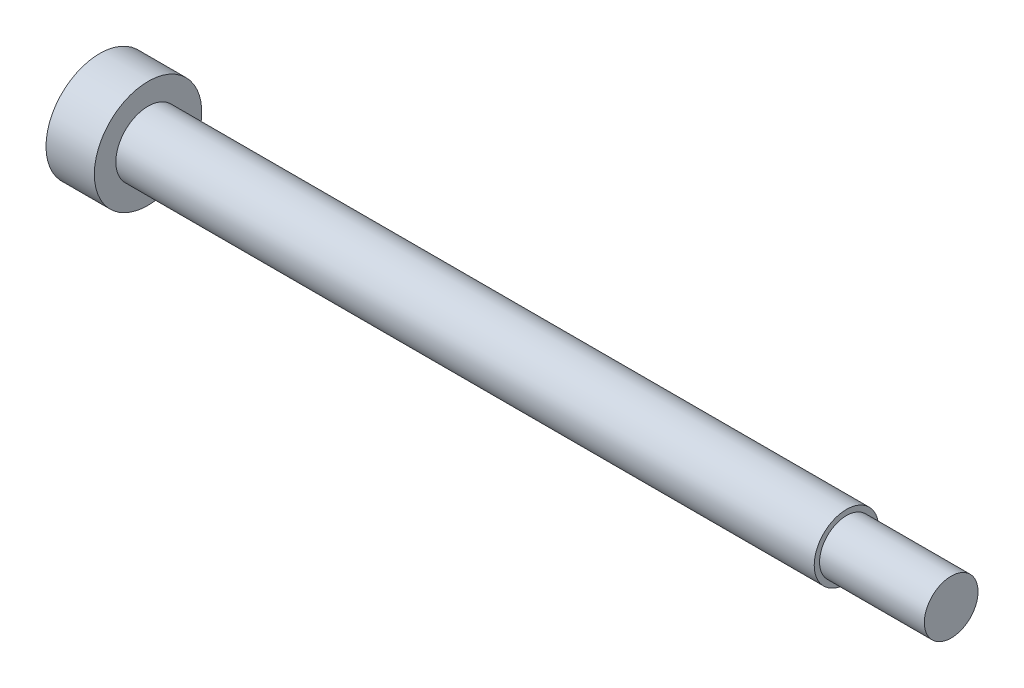
SolidWorks part; units mm, degrees
material "1060 合金"
ref_plane "前视基准面" through (0, 0, 0) normal (0, 0, 1) x (1, 0, 0)
ref_plane "上视基准面" through (0, 0, 0) normal (0, 1, 0) x (1, 0, 0)
ref_plane "右视基准面" through (0, 0, 0) normal (1, 0, 0) x (0, 0, -1)
other "Configuration Table"
sketch "草图1" plane through (0, 0, 0) normal (0, 0, 1) x (1, 0, 0)
  line L0 (0, 0) -> (10456.4321, 0) construction
  line L1 (0, 0) -> (0, 5)
  line L2 (0, 5) -> (4.5, 5)
  line L3 (4.5, 5) -> (4.5, 3)
  line L4 (4.5, 3) -> (69.5, 3)
  line L5 (69.5, 3) -> (69.5, 2.5)
  line L6 (69.5, 2.5) -> (79.25, 2.5)
  line L7 (79.25, 2.5) -> (79.25, 0)
  line L8 (79.25, 0) -> (0, 0)
  point P10 (76.1757, 1.3331)
  dimension "D1" = 5
  dimension "D2" = 3
  dimension "D3" = 4.5
  dimension "D4" = 65
  dimension "D5" = 2.5
  dimension "D6" = 9.75
revolve "旋转1" add sketch "草图1" angle 360 about L0
cosmetic thread "装饰螺纹线1" parameters "D2"=4
sketch "草图2" plane through (0, 0, 0) normal (-1, 0, 0) x (0, 0, 1)
  line L0 (0, 2.8868) -> (0, 0) construction
  line L1 (0, 2.8868) -> (-2.5, 1.4434)
  line L2 (-2.5, 1.4434) -> (-2.5, -1.4434)
  line L3 (-2.5, -1.4434) -> (0, -2.8868)
  line L4 (0, -2.8868) -> (2.5, -1.4434)
  line L5 (2.5, -1.4434) -> (2.5, 1.4434)
  line L6 (2.5, 1.4434) -> (0, 2.8868)
  circle A0 centre (0, 0) radius 2.5 construction
  dimension "D1" = 5
extrude "切除-拉伸1" cut sketch "草图2" against normal blind 3
